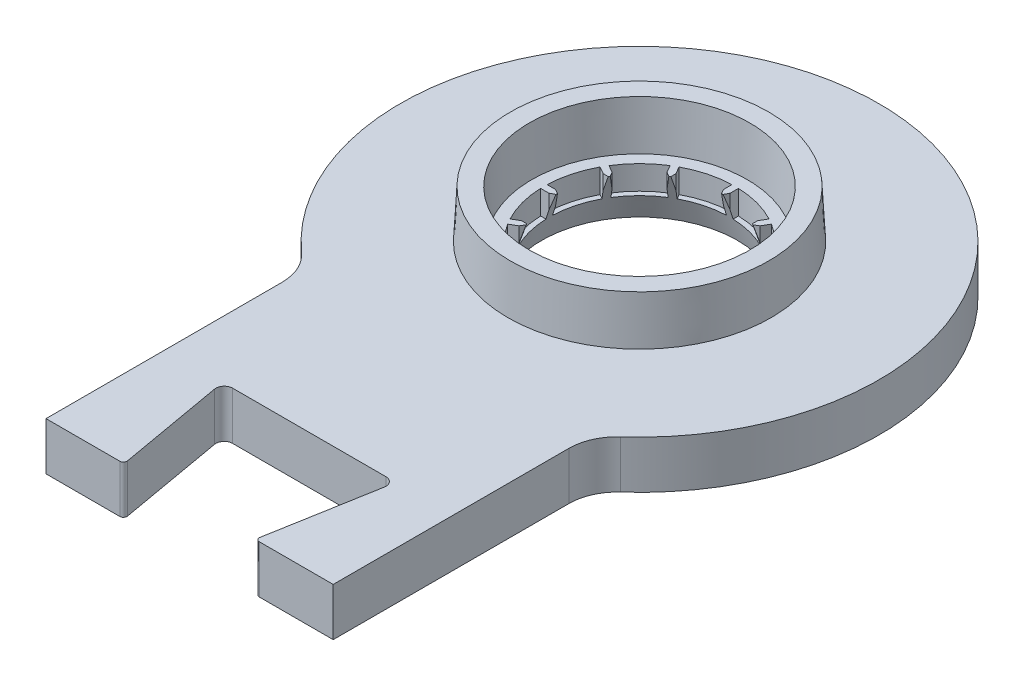
SolidWorks part; units mm, degrees
ref_plane "Front Plane" through (0, 0, 0) normal (0, 0, 1) x (1, 0, 0)
ref_plane "Top Plane" through (0, 0, 0) normal (0, 1, 0) x (1, 0, 0)
ref_plane "Right Plane" through (0, 0, 0) normal (1, 0, 0) x (0, 0, -1)
sketch "Sketch1" plane through (0, 0, 0) normal (0, 1, 0) x (1, 0, 0)
  line L0 (-6, 6) -> (-6, -13.2915)
  line L1 (-6, -19) -> (-2.7023, -19)
  line L2 (6, -19) -> (6, -13.2915)
  line L3 (6, 6) -> (-6, 6)
  line L4 (-6, -13.2915) -> (-6, -19)
  line L5 (6, -13.2915) -> (6, 6)
  line L6 (0, -19) -> (0, 0) construction
  line L7 (-2.6007, -19) -> (-3.5, -13.9) construction
  line L8 (-3.5, -13.9) -> (0, -13.9) construction
  line L9 (-2.7023, -19) -> (-3.6192, -13.8)
  line L10 (-3.6192, -13.8) -> (0, -13.8)
  line L11 (-2.6992, -19.0174) -> (-3.6192, -13.8) construction
  line L12 (2.7023, -19) -> (6, -19)
  line L13 (3.6192, -13.8) -> (0, -13.8)
  line L14 (2.7023, -19) -> (3.6192, -13.8)
  circle A0 centre (0, 0) radius 3.75
  dimension "D1" = 7.5
  dimension "D5" = 6
  dimension "D7" = 80
  dimension "D2" = 25
  dimension "D3" = 6
  dimension "D4" = 12
  dimension "D8" = 3.5
  dimension "D9" = 5.1
  dimension "D10" = 0.1
extrude "Boss-Extrude1" add sketch "Sketch1" along normal blind 2
sketch "Sketch2" plane through (0, 0, 0) normal (0, 1, 0) x (1, 0, 0)
  circle A0 centre (0, 0) radius 10
  circle A1 centre (0, 0) radius 3.8
  dimension "D1" = 20
  dimension "D2" = 7.6
extrude "Boss-Extrude2" add sketch "Sketch2" along normal blind 2
sketch "Sketch3" plane through (0, 0, 0) normal (0, -1, 0) x (1, 0, 0)
  line L0 (-3, 0) -> (-3, 4)
  line L1 (3, 0) -> (3, 4)
  arc A0 (-3, 0) -> (3, 0) centre (0, 0) ccw
  arc A1 (-3, 4) -> (3, 4) centre (0, 0) ccw
extrude "Boss-Extrude3" [suppressed] add sketch "Sketch3" along normal blind 4
fillet "Fillet1" [suppressed] radius 0.5
fillet "Fillet2" [suppressed] radius 1
sketch "Sketch4" plane through (0, 2, 0) normal (0, 1, 0) x (1, 0, 0)
  line L0 (-6, -8) -> (-6, -19) construction
  line L1 (-6, -18.8) -> (6, -18.8)
  line L2 (-6, -18.8) -> (-6, -19)
  line L3 (-6, -19) -> (6, -19)
  line L4 (6, -18.8) -> (6, -19)
  dimension "D1" = 0.2
extrude "Cut-Extrude1" cut sketch "Sketch4" against normal blind 4
fillet "Fillet3" radius 0.35 2 edges at (3.6192, 1, 13.8) (-3.6192, 1, 13.8)
fillet "Fillet4" radius 0.15 2 edges at (2.7375, 1, 18.8) (-2.7375, 1, 18.8)
sketch "Sketch5" plane through (0, 0, 0) normal (0, 1, 0) x (1, 0, 0)
  circle A1 centre (0, 0) radius 3
  circle A2 centre (0, 0) radius 2.1
  dimension "D1" = 4.2
  dimension "D2" = 6
extrude "Boss-Extrude4" [suppressed] add sketch "Sketch5" along normal blind 13
fillet "Fillet5" [suppressed] radius 2
fillet "Fillet6" radius 2 2 edges at (-6, 1, 8) (6, 1, 8)
sketch "Sketch6" plane through (0, 2, 0) normal (0, 1, 0) x (1, 0, 0)
  circle A0 centre (0, 0) radius 3.5
  dimension "D1" = 7
extrude "Boss-Extrude5" [suppressed] add sketch "Sketch6" along normal blind 2 contours A0
sketch "Sketch7" [suppressed] plane through (0, 4, 0) normal (0, 1, 0) x (1, 0, 0)
  circle A0 centre (0, 0) radius 3.15
extrude "Cut-Extrude3" [suppressed] cut sketch "Sketch7" against normal blind 3.2
fillet "Fillet7" [suppressed] radius 2
fillet "Fillet8" [suppressed] radius 1
fillet "Fillet9" [suppressed] radius 0.1
sketch "Sketch10" plane through (0, 2, 0) normal (0, 1, 0) x (1, 0, 0)
  circle A0 centre (0, 0) radius 4
  dimension "D1" = 8
extrude "Cut-Extrude4" cut sketch "Sketch10" against normal blind 1
sketch "Sketch8" plane through (0, 2, 0) normal (0, 1, 0) x (1, 0, 0)
  line L0 (0, 0) -> (0, 3.9) construction
  line L1 (-0.1363, 3.65) -> (0, 3.4)
  line L2 (-0.1363, 4.15) -> (0.1363, 4.15)
  line L3 (-0.1363, 4.15) -> (-0.1363, 3.65)
  line L4 (-0.1363, 3.65) -> (0.1363, 3.65) construction
  line L5 (0.1363, 4.15) -> (0.1363, 3.65)
  line L6 (-0.1363, 4.15) -> (0.1363, 3.65) construction
  line L7 (-0.1363, 3.65) -> (0.1363, 4.15) construction
  line L8 (0, 3.4) -> (0.1363, 3.65)
  dimension "D1" = 3.9
  dimension "D2" = 0.5
  dimension "D3" = 0.25
extrude "Boss-Extrude6" add sketch "Sketch8" against normal blind 2
pattern_circular "CirPattern1" count 12 every 30 about axis through (0, 0, 0) along (0, 1, 0) of "Boss-Extrude6"
sketch "Sketch9" plane through (0, 0, 0) normal (1, 0, 0) x (0, 0, -1)
  line L0 (3.4, 2.1848) -> (4.2, -0.3355)
  line L1 (4.2, -0.3355) -> (0, -0.3355)
  line L2 (3.4, 2.1848) -> (0, 2.1848)
  line L5 (0, 0) -> (0, 2) construction
  line L6 (0, 2.1848) -> (0, -0.3355)
  dimension "D2" = 4.2
  dimension "7.25/2" = 3.4
revolve "Cut-Revolve2" cut sketch "Sketch9" angle 360 about L5
sketch "Sketch11" plane through (0, 2, 0) normal (0, 1, 0) x (1, 0, 0)
  circle A0 centre (0, 0) radius 4.5
  circle A1 centre (0, 0) radius 5.5
  dimension "D1" = 9
  dimension "D2" = 11
extrude "Boss-Extrude7" add sketch "Sketch11" along normal blind 2 draft 3
